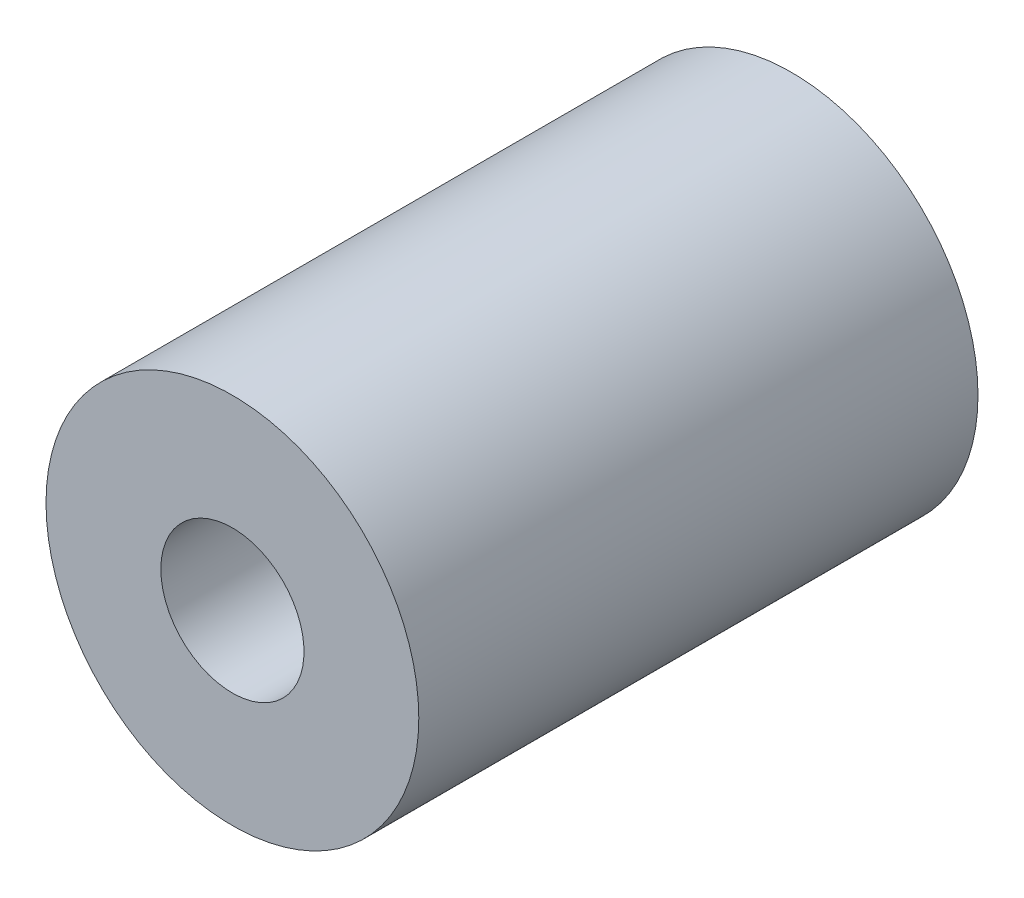
SolidWorks part; units mm, degrees
ref_plane "Front Plane" through (0, 0, 0) normal (0, 0, 1) x (1, 0, 0)
ref_plane "Top Plane" through (0, 0, 0) normal (0, 1, 0) x (1, 0, 0)
ref_plane "Right Plane" through (0, 0, 0) normal (1, 0, 0) x (0, 0, -1)
sketch "Sketch1" plane through (0, 0, 0) normal (0, 0, 1) x (1, 0, 0)
  circle A0 centre (0, 0) radius 6.35
  circle A1 centre (0, 0) radius 2.4384
  dimension "OD" = 12.7
  dimension "ID" = 4.8768
extrude "Extrude1" add sketch "Sketch1" along normal mid plane 19.05
sketch "Sketch2" plane through (0, 0, 0) normal (1, 0, 0) x (0, 0, -1)
  line L0 (-9.525, -2.4384) -> (9.525, -2.4384) construction
  line L3 (9.525, 2.4384) -> (-9.525, 2.4384) construction
  line L5 (-9.525, -2.4384) -> (9.525, -2.4384)
  line L6 (9.525, 2.4384) -> (-9.525, 2.4384)
sketch "Sketch4" plane through (0, 0, 9.525) normal (0, 0, 1) x (1, 0, 0)
  line L0 (0, 0) -> (-1.7242, 1.7242)
  line L1 (0, -6.985) -> (0, 6.985) construction
  circle A0 centre (0, 0) radius 2.4384 construction
  dimension "D1" = 45
